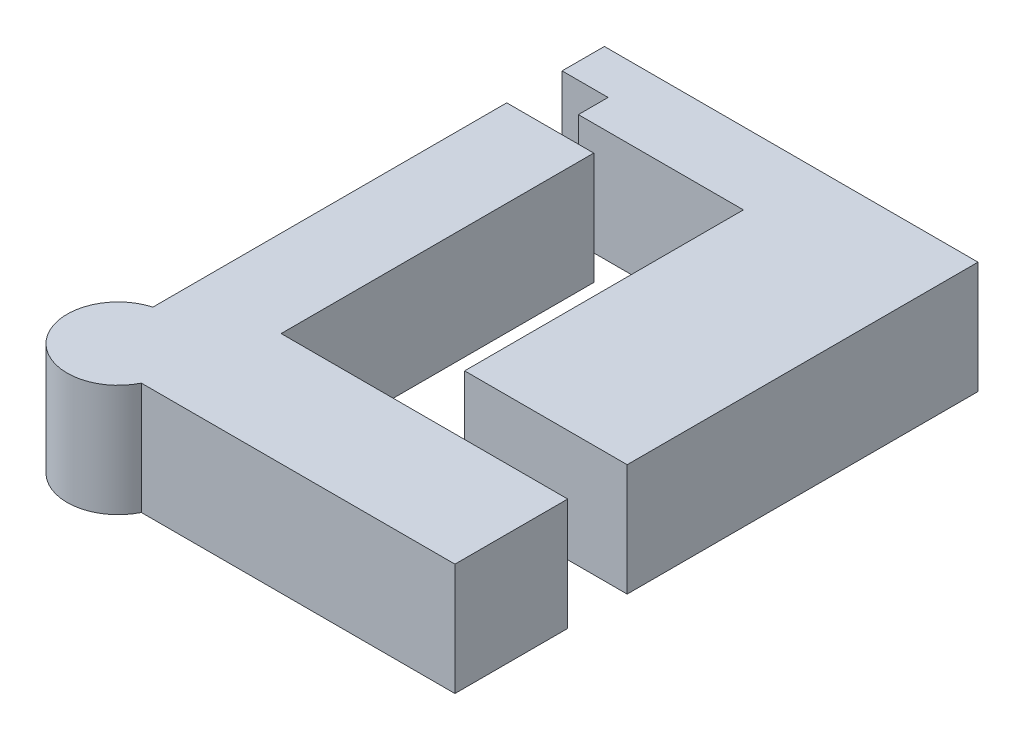
SolidWorks part; units mm, degrees
ref_plane "前视基准面" through (0, 0, 0) normal (0, 0, 1) x (1, 0, 0)
ref_plane "上视基准面" through (0, 0, 0) normal (0, 1, 0) x (1, 0, 0)
ref_plane "右视基准面" through (0, 0, 0) normal (1, 0, 0) x (0, 0, -1)
sketch "草图1" plane through (0, 0, 0) normal (0, 1, 0) x (1, 0, 0)
  line L0 (-90.2395, 25.2882) -> (-66.9471, 25.2882)
  line L1 (-90.2395, 51.4264) -> (9.7605, 51.4264) construction
  line L2 (-90.2395, 51.4264) -> (-90.2395, -69.4033) construction
  line L3 (-74.1675, -88.5736) -> (9.7605, -88.5736) construction
  line L4 (9.7605, 51.4264) -> (9.7605, -88.5736) construction
  line L5 (-66.9471, 25.2882) -> (-66.9471, -58.3859)
  line L6 (-66.9471, -58.3859) -> (9.7605, -58.3859)
  line L7 (-90.2395, 51.4264) -> (9.7605, 51.4264)
  line L8 (9.7605, 51.4264) -> (9.7605, -42.4741)
  line L9 (9.7605, -42.4741) -> (-33.7518, -42.4741)
  line L10 (-33.7518, -42.4741) -> (-33.7518, 32.1468)
  line L11 (-33.7518, 32.1468) -> (-77.9207, 32.1468)
  line L12 (-77.9207, 32.1468) -> (-77.9207, 40.1027)
  line L13 (-77.9207, 40.1027) -> (-90.2395, 40.1027)
  line L14 (-90.2395, 40.1027) -> (-90.2395, 51.4264)
  line L15 (-90.2395, 25.2882) -> (-90.2395, -69.4033)
  line L16 (-74.1675, -88.5736) -> (9.7605, -88.5736)
  line L17 (9.7605, -88.5736) -> (9.7605, -58.3859)
  arc A0 (-90.2395, -69.4033) -> (-74.1675, -88.5736) centre (-86.4253, -82.528) ccw
  dimension "D2" = 100
extrude "凸台-拉伸1" add sketch "草图1" along normal blind 30
